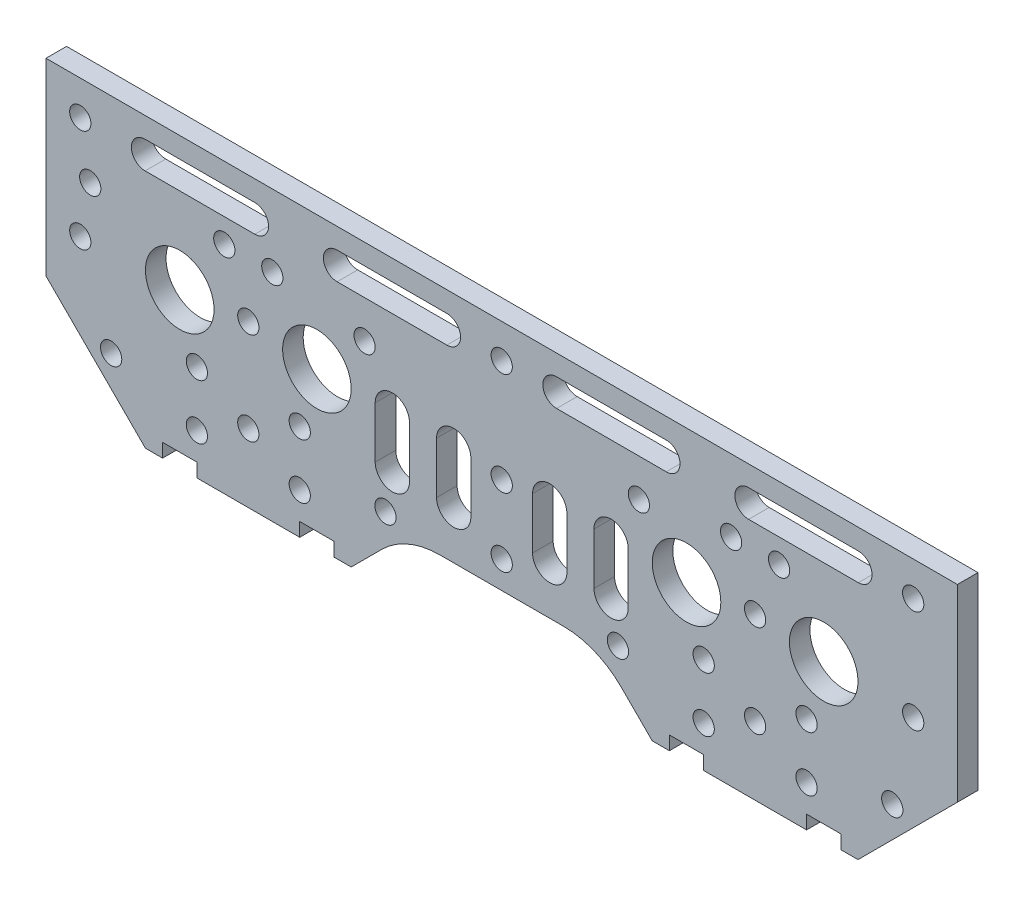
SolidWorks part; units mm, degrees
material "Thornel Mat VMA"
ref_plane "前视基准面" through (0, 0, 0) normal (0, 0, 1) x (1, 0, 0)
ref_plane "上视基准面" through (0, 0, 0) normal (0, 1, 0) x (1, 0, 0)
ref_plane "右视基准面" through (0, 0, 0) normal (1, 0, 0) x (0, 0, -1)
sketch "草图1" plane through (0, 0, 0) normal (0, 0, 1) x (1, 0, 0)
  line L0 (0, 7) -> (0, 0) construction
  line L1 (7.5, -4) -> (-7.5, -4) construction
  line L2 (7.5, -4) -> (7.5, 4) construction
  line L3 (7.5, 4) -> (-7.5, 4) construction
  line L4 (-7.5, -4) -> (-7.5, 4) construction
  line L5 (7.5, -4) -> (-7.5, 4) construction
  line L6 (7.5, 4) -> (-7.5, -4) construction
  line L7 (13.5, 4) -> (-13.5, 4) construction
  line L8 (13.5, 4) -> (13.5, 10) construction
  line L9 (13.5, 10) -> (-13.5, 10) construction
  line L10 (-13.5, 4) -> (-13.5, 10) construction
  line L11 (13.5, 4) -> (-13.5, 10) construction
  line L12 (13.5, 10) -> (-13.5, 4) construction
  line L13 (0, 0) -> (73.9, 0) construction
  line L14 (73.9, 7) -> (73.9, 0) construction
  line L15 (81.4, -4) -> (66.4, -4) construction
  line L16 (81.4, -4) -> (81.4, 4) construction
  line L17 (81.4, 4) -> (66.4, 4) construction
  line L18 (66.4, -4) -> (66.4, 4) construction
  line L19 (81.4, -4) -> (66.4, 4) construction
  line L20 (81.4, 4) -> (66.4, -4) construction
  line L21 (87.4, 4) -> (60.4, 4) construction
  line L22 (87.4, 4) -> (87.4, 10) construction
  line L23 (87.4, 10) -> (60.4, 10) construction
  line L24 (60.4, 4) -> (60.4, 10) construction
  line L25 (87.4, 4) -> (60.4, 10) construction
  line L26 (87.4, 10) -> (60.4, 4) construction
  line L27 (-29.5, 32) -> (103.4, 32)
  line L28 (86.4, -10) -> (61.4, -10)
  line L29 (-12.5, -10) -> (-29.5, 7) construction
  line L30 (-29.5, 7) -> (-29.5, 32)
  line L31 (103.4, 32) -> (103.4, 7)
  line L33 (103.4, 7) -> (86.4, -10) construction
  line L34 (-24.5, 27) -> (-24.5, 12) construction
  line L35 (-29.5, 19.5) -> (-24.5, 19.5) construction
  line L36 (-24.5, 19.5) -> (96.95, 19.5) construction
  line L37 (36.95, -10) -> (36.95, 19.5) construction
  line L38 (-23.05, 27) -> (-23.05, 12) construction
  line L39 (36.95, 27) -> (36.95, 12) construction
  line L40 (96.95, 27) -> (96.95, 12) construction
  line L44 (3.1432, -12.9153) -> (30.0133, -39.7853) construction
  line L52 (-15.05, 27) -> (0.95, 27) construction
  line L53 (-15.05, 29) -> (0.95, 29)
  line L54 (-15.05, 25) -> (0.95, 25)
  line L55 (12.95, 27) -> (28.95, 27) construction
  line L56 (12.95, 29) -> (28.95, 29)
  line L57 (12.95, 25) -> (28.95, 25)
  line L58 (44.95, 27) -> (60.95, 27) construction
  line L59 (44.95, 29) -> (60.95, 29)
  line L60 (44.95, 25) -> (60.95, 25)
  line L61 (72.95, 27) -> (88.95, 27) construction
  line L62 (72.95, 29) -> (88.95, 29)
  line L63 (72.95, 25) -> (88.95, 25)
  line L64 (23, -2) -> (50.9, -2)
  line L65 (51.9757, -0.5757) -> (61.4, -10) construction
  line L66 (12.5, -10) -> (-12.5, -10)
  line L67 (12.5, -10) -> (61.4, -10) construction
  line L68 (21, 12.5) -> (21, 5) construction
  line L69 (23.5, 12.5) -> (23.5, 5)
  line L70 (18.5, 12.5) -> (18.5, 5)
  line L71 (29.95, 12.5) -> (29.95, 5) construction
  line L72 (32.45, 12.5) -> (32.45, 5)
  line L73 (27.45, 12.5) -> (27.45, 5)
  line L74 (52.9, 12.5) -> (52.9, 5) construction
  line L75 (50.4, 12.5) -> (50.4, 5)
  line L76 (55.4, 12.5) -> (55.4, 5)
  line L77 (43.95, 12.5) -> (43.95, 5) construction
  line L78 (41.45, 12.5) -> (41.45, 5)
  line L79 (46.45, 12.5) -> (46.45, 5)
  line L80 (-29.5, 7) -> (-29.5, 4.5)
  line L81 (-29.5, 4.5) -> (-15, -10)
  line L82 (-15, -10) -> (-12.5, -10)
  line L83 (86.4, -10) -> (88.9, -10)
  line L84 (88.9, -10) -> (103.4, 4.5)
  line L85 (103.4, 4.5) -> (103.4, 7)
  line L87 (15, -10) -> (23, -2)
  line L88 (12.5, -10) -> (20.5, -2) construction
  line L89 (20.5, -2) -> (23, -2) construction
  line L90 (12.5, -10) -> (15, -10)
  line L91 (61.4, -10) -> (58.9, -10)
  line L92 (58.9, -10) -> (50.9, -2)
  circle A0 centre (-7.5, 4) radius 1.55
  circle A1 centre (-7.5, -4) radius 1.55
  circle A2 centre (7.5, -4) radius 1.55
  circle A3 centre (7.5, 4) radius 1.55
  circle A4 centre (66.4, 4) radius 1.55
  circle A5 centre (66.4, -4) radius 1.55
  circle A6 centre (81.4, 4) radius 1.55
  circle A7 centre (81.4, -4) radius 1.55
  circle A8 centre (-24.5, 27) radius 1.55
  circle A9 centre (-24.5, 12) radius 1.55
  circle A10 centre (36.95, 19.5) radius 1.55 construction
  circle A11 centre (16.95, 19.5) radius 1.55
  circle A12 centre (-3.05, 19.5) radius 1.55 construction
  circle A15 centre (-23.05, 27) radius 1.55 construction
  circle A16 centre (-23.05, 12) radius 1.55 construction
  circle A17 centre (36.95, 27) radius 1.55
  circle A18 centre (36.95, 12) radius 1.55
  circle A19 centre (56.95, 19.5) radius 1.55
  circle A20 centre (76.95, 19.5) radius 1.55 construction
  circle A21 centre (-23.05, 19.5) radius 1.55 construction
  circle A22 centre (-43.05, 19.5) radius 1.55 [skipped]
  circle A24 centre (96.95, 27) radius 1.55
  circle A25 centre (96.95, 12) radius 1.55
  circle A28 centre (30.0133, -39.7853) radius 4.5 construction
  arc A31 (-15.05, 29) -> (-15.05, 25) centre (-15.05, 27) ccw
  arc A32 (0.95, 25) -> (0.95, 29) centre (0.95, 27) ccw
  arc A33 (12.95, 29) -> (12.95, 25) centre (12.95, 27) ccw
  arc A34 (28.95, 25) -> (28.95, 29) centre (28.95, 27) ccw
  arc A35 (44.95, 29) -> (44.95, 25) centre (44.95, 27) ccw
  arc A36 (60.95, 25) -> (60.95, 29) centre (60.95, 27) ccw
  arc A37 (72.95, 29) -> (72.95, 25) centre (72.95, 27) ccw
  arc A38 (88.95, 25) -> (88.95, 29) centre (88.95, 27) ccw
  circle A39 centre (-23.05, 19.5) radius 1.55
  circle A40 centre (36.95, 2) radius 1.55
  arc A41 (23.5, 12.5) -> (18.5, 12.5) centre (21, 12.5) ccw
  arc A42 (18.5, 5) -> (23.5, 5) centre (21, 5) ccw
  arc A43 (32.45, 12.5) -> (27.45, 12.5) centre (29.95, 12.5) ccw
  arc A44 (27.45, 5) -> (32.45, 5) centre (29.95, 5) ccw
  arc A45 (50.4, 12.5) -> (55.4, 12.5) centre (52.9, 12.5) cw
  arc A46 (55.4, 5) -> (50.4, 5) centre (52.9, 5) cw
  arc A47 (41.45, 12.5) -> (46.45, 12.5) centre (43.95, 12.5) cw
  arc A48 (46.45, 5) -> (41.45, 5) centre (43.95, 5) cw
  circle A49 centre (73.9, 13.5) radius 1.55
  circle A50 centre (70.4, 21.5) radius 1.55
  circle A51 centre (77.4, 21.5) radius 1.55
  circle A52 centre (0, 13.5) radius 1.55
  circle A53 centre (-3.5, 21.5) radius 1.55
  circle A54 centre (3.5, 21.5) radius 1.55
  circle A55 centre (-20, -0.5) radius 1.55
  circle A56 centre (93.9, -0.5) radius 1.55
  circle A57 centre (20, -0.5) radius 1.55
  circle A58 centre (53.9, -0.5) radius 1.55
  circle A59 centre (0, 0) radius 1.55
  circle A61 centre (73.9, 0) radius 1.55
  circle A62 centre (-10, 12.5) radius 5
  circle A63 centre (83.9, 12.5) radius 5
  circle A64 centre (10, 12.5) radius 5
  circle A65 centre (63.9, 12.5) radius 5
  point P0 (0, 0)
  point P10 (0, 7)
  point P22 (73.9, 7)
  point P85 (21, 8.75)
  point P87 (-7.05, 27)
  point P94 (20.95, 27)
  point P101 (52.95, 27)
  point P108 (80.95, 27)
  point P118 (29.95, 8.75)
  point P130 (52.9, 8.75)
  point P137 (43.95, 8.75)
  dimension "D1" = 3.1
  dimension "D16" = 15
  dimension "D24" = 16
  dimension "D22" = 2
  dimension "D27" = 12
  dimension "D36" = 2.5
  dimension "D44" = 3.1
  dimension "D47" = 10
  dimension "D2" = 15
  dimension "D3" = 8
  dimension "D4" = 6
  dimension "D5" = 3
  dimension "D6" = 27
  dimension "D7" = 73.9
  dimension "D8" = 20
  dimension "D9" = 29.5
  dimension "D10" = 6
  dimension "D11" = 25
  dimension "D12" = 12.5
  dimension "D13" = 12.5
  dimension "D14" = 25
  dimension "D15" = 5
  dimension "D18" = 20
  dimension "D20" = 20
  dimension "D21" = 20
  dimension "D23" = 17
  dimension "D25" = 9
  dimension "D26" = 38
  dimension "D28" = 4
  dimension "D29" = 16
  dimension "D30" = 16
  dimension "D31" = 16
  dimension "D32" = 16
  dimension "D33" = 7
  dimension "D34" = 7
  dimension "D35" = 5
  dimension "D37" = 7
  dimension "D38" = 7
  dimension "D39" = 2
  dimension "D40" = 8
  dimension "D41" = 7
  dimension "D42" = 7.5
  dimension "D43" = 7.5
  dimension "D45" = 2.5
  dimension "D46" = 2.5
  dimension "D48" = 10
  dimension "D49" = 7
  dimension "D50" = 2.5
  dimension "D17" = 5
  dimension "D19" = 3
extrude "凸台-拉伸1" add sketch "草图1" along normal blind 3
fillet "圆角1" radius 12 2 edges at (50.9, -2, 1.5) (23, -2, 1.5)
sketch "草图2" plane through (0, 0, 3) normal (0, 0, 1) x (1, 0, 0)
  line L0 (0, 0) -> (0, -20.5698) construction
  line L1 (-7.5, -16) -> (-12.5, -16)
  line L2 (-7.5, -16) -> (-7.5, -8)
  line L3 (-7.5, -8) -> (-12.5, -8)
  line L4 (-12.5, -16) -> (-12.5, -8)
  line L5 (-7.5, -16) -> (-12.5, -8) construction
  line L6 (-7.5, -8) -> (-12.5, -16) construction
  line L7 (7.5, -8) -> (12.5, -8)
  line L8 (12.5, -16) -> (12.5, -8)
  line L9 (7.5, -16) -> (12.5, -16)
  line L10 (7.5, -16) -> (7.5, -8)
  line L11 (10, -8) -> (10, -14.8959) construction
  line L12 (-15, -10) -> (15, -10) construction
  line L13 (36.95, -2) -> (36.95, -14.1262) construction
  line L14 (27.9706, -2) -> (45.9294, -2) construction
  line L15 (81.4, -8) -> (86.4, -8)
  line L16 (86.4, -16) -> (86.4, -8)
  line L17 (81.4, -16) -> (86.4, -16)
  line L18 (81.4, -16) -> (81.4, -8)
  line L19 (66.4, -16) -> (66.4, -8)
  line L20 (66.4, -16) -> (61.4, -16)
  line L21 (61.4, -16) -> (61.4, -8)
  line L22 (66.4, -8) -> (61.4, -8)
  point P0 (-10, -12)
  dimension "D1" = 20
  dimension "D2" = 2
  dimension "D3" = 8
  dimension "D4" = 5
extrude "切除-拉伸1" cut sketch "草图2" against normal blind 10
